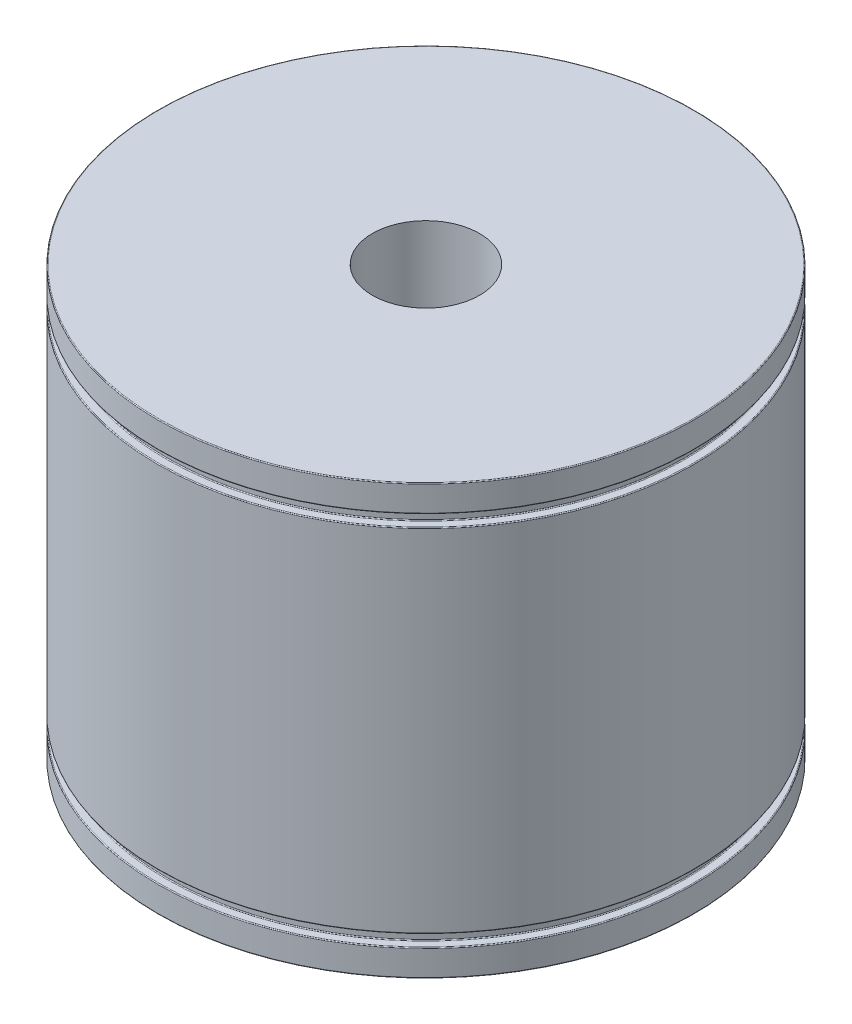
SolidWorks part; units mm, degrees
ref_plane "Alzado" through (0, 0, 0) normal (0, 0, 1) x (1, 0, 0)
ref_plane "Planta" through (0, 0, 0) normal (0, 1, 0) x (1, 0, 0)
ref_plane "Vista lateral" through (0, 0, 0) normal (1, 0, 0) x (0, 0, -1)
sketch "Croquis1" plane through (0, 0, 0) normal (0, 0, 1) x (1, 0, 0)
  line L0 (0, 25.4) -> (0, -33.306) construction
  line L1 (6.35, 25.4) -> (6.35, -25.4)
  line L2 (6.35, 25.4) -> (31.65, 25.4)
  line L3 (31.75, 25.3) -> (31.75, 22.3333)
  line L4 (31.65, 22.2333) -> (30.7986, 22.2333)
  line L5 (30.6986, 22.1333) -> (30.6986, 20.9362)
  line L6 (30.7986, 20.8362) -> (31.65, 20.8362)
  line L7 (-13.2073, 0) -> (4.6457, 0) construction
  line L8 (30.7986, -20.8362) -> (31.65, -20.8362)
  line L9 (30.6986, -22.1333) -> (30.6986, -20.9362)
  line L10 (31.65, -22.2333) -> (30.7986, -22.2333)
  line L11 (31.75, -25.3) -> (31.75, -22.3333)
  line L12 (31.65, -25.4) -> (6.35, -25.4)
  line L13 (31.75, 20.7362) -> (31.75, -20.7362)
  arc A0 (31.75, -25.3) -> (31.65, -25.4) centre (31.65, -25.3) cw
  arc A1 (31.65, 20.8362) -> (31.75, 20.7362) centre (31.65, 20.7362) cw
  arc A2 (30.6986, 20.9362) -> (30.7986, 20.8362) centre (30.7986, 20.9362) ccw
  arc A3 (30.7986, 22.2333) -> (30.6986, 22.1333) centre (30.7986, 22.1333) ccw
  arc A4 (31.75, 22.3333) -> (31.65, 22.2333) centre (31.65, 22.3333) cw
  arc A5 (31.65, 25.4) -> (31.75, 25.3) centre (31.65, 25.3) cw
  arc A6 (30.6986, -22.1333) -> (30.7986, -22.2333) centre (30.7986, -22.1333) ccw
  arc A7 (31.65, -22.2333) -> (31.75, -22.3333) centre (31.65, -22.3333) cw
  arc A8 (31.65, -20.8362) -> (31.75, -20.7362) centre (31.65, -20.7362) ccw
  arc A9 (30.7986, -20.8362) -> (30.6986, -20.9362) centre (30.7986, -20.9362) ccw
  point P19 (31.75, -25.4)
  point P22 (31.75, 20.8362)
  point P25 (30.6986, 20.8362)
  point P28 (30.6986, 22.2333)
  point P31 (31.75, 22.2333)
  point P34 (31.75, 25.4)
  point P37 (30.6986, -22.2333)
  point P40 (31.75, -22.2333)
  point P43 (31.75, -20.8362)
  point P46 (30.6986, -20.8362)
  dimension "D3" = 0.1
  dimension "D1" = 50.8
  dimension "D2" = 31.75
  dimension "D4" = 12.7
revolve "Revolución1" add sketch "Croquis1" angle 360 about L0
